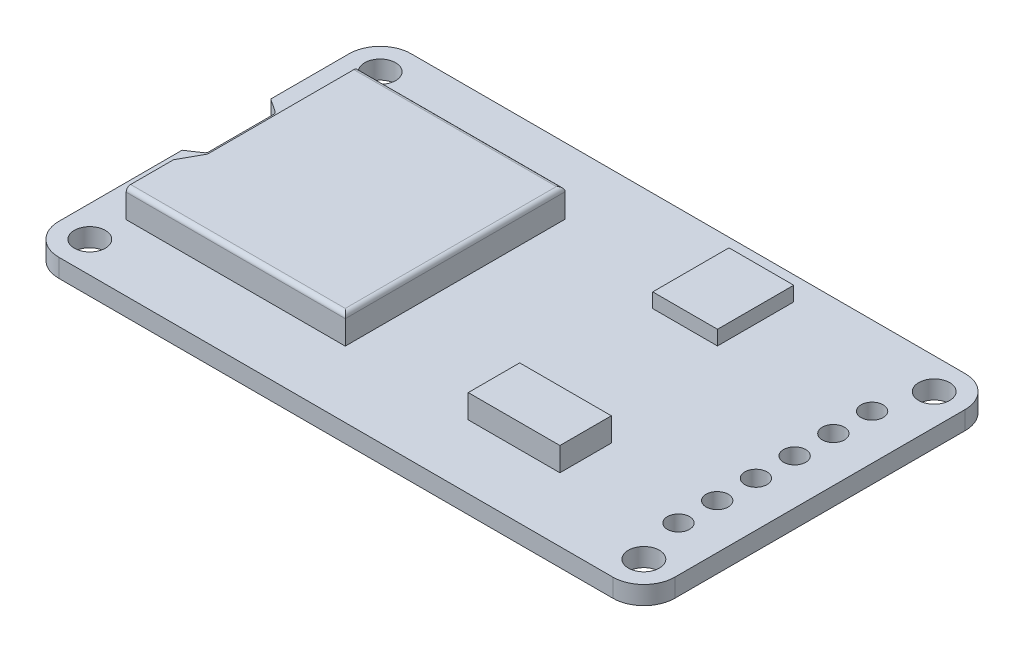
SolidWorks part; units mm, degrees
ref_plane "Plan de face" through (0, 0, 0) normal (0, 0, 1) x (1, 0, 0)
ref_plane "Plan de dessus" through (0, 0, 0) normal (0, 1, 0) x (1, 0, 0)
ref_plane "Plan de droite" through (0, 0, 0) normal (1, 0, 0) x (0, 0, -1)
sketch "Esquisse1" plane through (0, 0, 0) normal (0, 1, 0) x (1, 0, 0)
  line L0 (-18.74, 11.92) -> (18.74, 11.92)
  line L1 (20.84, 9.82) -> (20.84, -9.82)
  line L2 (18.74, -11.92) -> (-18.74, -11.92)
  line L4 (-20.84, 9.82) -> (-20.84, 4.52)
  line L5 (-20.84, 4.52) -> (-19.9514, 3.9281)
  line L6 (-19.84, 3.72) -> (-19.84, -0.68)
  line L7 (-19.9514, -0.8881) -> (-20.84, -1.48)
  line L8 (-20.84, -1.48) -> (-20.84, -9.82)
  arc A0 (18.74, 11.92) -> (20.84, 9.82) centre (18.74, 9.82) cw
  arc A1 (20.84, -9.82) -> (18.74, -11.92) centre (18.74, -9.82) cw
  arc A2 (-18.74, -11.92) -> (-20.84, -9.82) centre (-18.74, -9.82) cw
  arc A3 (-20.84, 9.82) -> (-18.74, 11.92) centre (-18.74, 9.82) cw
  circle A4 centre (-18.74, 9.82) radius 1.05
  circle A5 centre (18.74, 9.82) radius 1.05
  circle A6 centre (-18.74, -9.82) radius 1.05
  circle A7 centre (18.74, -9.82) radius 1.05
  arc A8 (-19.9514, 3.9281) -> (-19.84, 3.72) centre (-20.09, 3.72) cw
  arc A9 (-19.84, -0.68) -> (-19.9514, -0.8881) centre (-20.09, -0.68) cw
  point P12 (0, 11.92)
  point P13 (0, -11.92)
  point P14 (20.2249, -11.3049)
  point P17 (20.84, 0)
  point P18 (-20.2249, 11.3049)
  point P29 (-19.84, 1.52)
  point P31 (-20.84, 7.17)
  point P32 (-20.84, -5.65)
  dimension "D3" = 2.1
  dimension "D4" = 2.1
  dimension "D5" = 2.1
  dimension "D6" = 2.1
  dimension "D7" = 2.1
  dimension "D11" = 0.25
  dimension "D12" = 0.25
  dimension "D1" = 23.84
  dimension "D2" = 6
  dimension "D8" = 4.4
  dimension "D9" = 1
  dimension "D10" = 3
  dimension "D13" = 41.68
  dimension "D14" = 7.4
extrude "Plaque" add sketch "Esquisse1" along normal blind 1.24
sketch "Esquisse2" plane through (0, 1.24, 0) normal (0, 1, 0) x (1, 0, 0)
  line L0 (-18.66, -7.44) -> (-3.84, -7.44)
  line L1 (-3.84, -7.44) -> (-3.84, 7.44)
  line L2 (-3.84, 7.44) -> (-17.84, 7.44)
  line L3 (-17.84, 7.44) -> (-17.84, -2.7563)
  line L4 (-17.84, -2.7563) -> (-18.66, -4.24)
  line L5 (-18.66, -4.24) -> (-18.66, -7.44)
  line L12 (-20.84, 9.82) -> (-20.84, 4.52) construction
  point P2 (-3.84, 0)
  dimension "D1" = 14.88
  dimension "D2" = 14.82
  dimension "D3" = 3.2
  dimension "D4" = 1.4837
  dimension "D5" = 14
  dimension "D6" = 3
extrude "Carte SD" add sketch "Esquisse2" along normal blind 1.91
sketch "Esquisse4" plane through (0, 1.24, 0) normal (0, 1, 0) x (1, 0, 0)
  line L7 (4.64, -7.6) -> (10.84, -7.6)
  line L8 (4.64, -7.6) -> (4.64, -4.12)
  line L9 (4.64, -4.12) -> (10.84, -4.12)
  line L10 (10.84, -7.6) -> (10.84, -4.12)
  line L11 (4.64, -7.6) -> (10.84, -4.12) construction
  line L12 (4.64, -4.12) -> (10.84, -7.6) construction
  line L13 (20.84, -9.82) -> (20.84, 9.82) construction
  line L14 (-18.74, -11.92) -> (18.74, -11.92) construction
  point P5 (7.74, -5.86)
  dimension "D5" = 7.8
  dimension "D6" = 3.48
  dimension "D7" = 6.2
  dimension "D8" = 10
extrude "Puce" add sketch "Esquisse4" along normal blind 1.6 contours L7 L10 L9 L8
sketch "Esquisse7" plane through (0, 1.24, 0) normal (0, 1, 0) x (1, 0, 0)
  line L0 (18.74, 11.92) -> (-18.74, 11.92) construction
  line L1 (4.36, 10.32) -> (8.74, 10.32)
  line L2 (4.36, 10.32) -> (4.36, 5.16)
  line L3 (4.36, 5.16) -> (8.74, 5.16)
  line L4 (8.74, 10.32) -> (8.74, 5.16)
  line L5 (4.36, 10.32) -> (8.74, 5.16) construction
  line L6 (4.36, 5.16) -> (8.74, 10.32) construction
  line L7 (20.84, -9.82) -> (20.84, 9.82) construction
  point P0 (6.55, 7.74)
  dimension "D1" = 1.6
  dimension "D2" = 5.16
  dimension "D3" = 4.38
  dimension "D4" = 12.1
extrude "Puce 2" add sketch "Esquisse7" along normal blind 0.98
sketch "Esquisse8" plane through (0, 1.24, 0) normal (0, 1, 0) x (1, 0, 0)
  line L0 (20.84, -9.82) -> (20.84, 9.82) construction
  line L1 (18.74, 11.92) -> (-18.74, 11.92) construction
  circle A5 centre (17.79, 6.57) radius 0.75
  circle A6 centre (17.79, 3.95) radius 0.75
  circle A7 centre (17.79, 1.33) radius 0.75
  circle A8 centre (17.79, -1.29) radius 0.75
  circle A9 centre (17.79, -3.91) radius 0.75
  circle A10 centre (17.79, -6.53) radius 0.75
  point P0 (18.54, 6.57)
  point P3 (17.79, 7.32)
  dimension "D1" = 1.5
  dimension "D2" = 2.3
  dimension "D3" = 4.6
  dimension "D4" = 6
extrude "Enlèv. mat.-Extru.1" cut sketch "Esquisse8" against normal through all
sketch "Esquisse9" plane through (-17.84, 0, 0) normal (-1, 0, 0) x (0, 0, 1)
  line L0 (-7.44, 3.15) -> (-7.44, 1.24) construction
  line L1 (-6.57, 2.95) -> (4.73, 2.95)
  line L2 (-6.57, 2.95) -> (-6.57, 1.75)
  line L3 (-6.57, 1.75) -> (4.73, 1.75)
  line L4 (4.73, 2.95) -> (4.73, 1.75)
  line L5 (-7.44, 3.15) -> (2.7563, 3.15) construction
  dimension "D1" = 0.87
  dimension "D2" = 11.3
  dimension "D3" = 1.2
  dimension "D4" = 0.2
extrude "Enlèv. mat.-Extru.3" cut sketch "Esquisse9" against normal blind 11.8 and the other way up to surface other way up to face at (-18.66, 2.195, 5.84)
fillet "Congé1" radius 0.3 3 edges at (-10.84, 3.15, -7.44) (-3.84, 3.15, 0) (-11.25, 3.15, 7.44)
